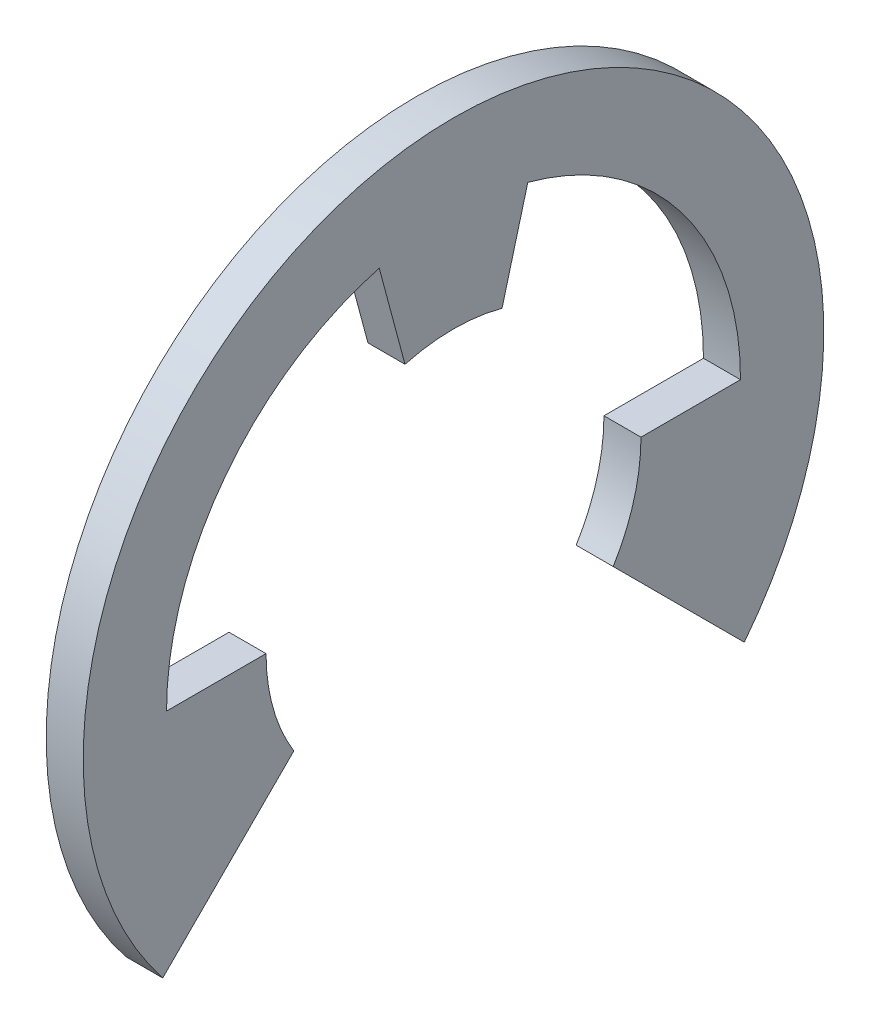
SolidWorks part; units mm, degrees
ref_plane "Front Plane" through (0, 0, 0) normal (0, 0, 1) x (1, 0, 0)
ref_plane "Top Plane" through (0, 0, 0) normal (0, 1, 0) x (1, 0, 0)
ref_plane "Right Plane" through (0, 0, 0) normal (1, 0, 0) x (0, 0, -1)
sketch "Sketch1" plane through (0, 0, 0) normal (1, 0, 0) x (0, 0, -1)
  line L0 (-4.05, 0) -> (-6.2, 0)
  line L1 (-1.0482, 3.912) -> (-1.6047, 5.9887)
  line L2 (4.05, 0) -> (6.2, 0)
  line L3 (1.6047, 5.9887) -> (1.0482, 3.912)
  line L4 (-3.45, -2.1213) -> (-6.282, -4.9534)
  line L5 (3.45, -2.1213) -> (6.282, -4.9534)
  line L9 (0, 0) -> (0, 8) construction
  arc A0 (-4.05, 0) -> (-3.45, -2.1213) centre (0, 0) ccw
  arc A1 (6.282, -4.9534) -> (-6.282, -4.9534) centre (0, 0) ccw
  arc A2 (6.2, 0) -> (1.6047, 5.9887) centre (0, 0) ccw
  arc A3 (1.0482, 3.912) -> (-1.0482, 3.912) centre (0, 0) ccw
  arc A4 (-1.6047, 5.9887) -> (-6.2, 0) centre (0, 0) ccw
  arc A5 (3.45, -2.1213) -> (4.05, 0) centre (0, 0) ccw
  circle A6 centre (0, 0) radius 4.05 construction
  dimension "D1" = 30
  dimension "D2" = 90
  dimension "REE_D" = 16
  dimension "REE_D_s" = 8.1
  dimension "REE_B_s" = 1.8
  dimension "REE_H" = 6.9
extrude "Boss-Extrude1" add sketch "Sketch1" along normal blind 0.8
